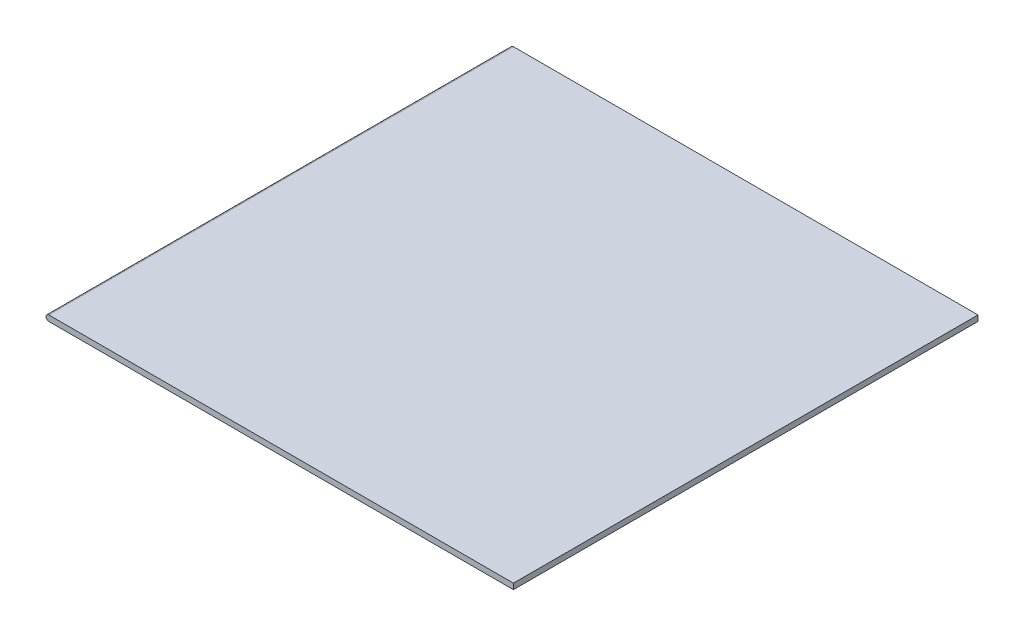
SolidWorks part; units mm, degrees
ref_plane "Спереди" through (0, 0, 0) normal (0, 0, 1) x (1, 0, 0)
ref_plane "Сверху" through (0, 0, 0) normal (0, 1, 0) x (1, 0, 0)
ref_plane "Справа" through (0, 0, 0) normal (1, 0, 0) x (0, 0, -1)
other "Configuration Table"
sketch "Эскиз1" plane through (0, 0, 0) normal (0, 1, 0) x (1, 0, 0)
  line L1 (-205, -205) -> (205, -205)
  line L2 (-205, -205) -> (-205, 205)
  line L3 (-205, 205) -> (205, 205)
  line L4 (205, -205) -> (205, 205)
  line L5 (-205, -205) -> (205, 205) construction
  line L6 (-205, 205) -> (205, -205) construction
  point P0 (0, 0)
  dimension "D1" = 410
extrude "Бобышка-Вытянуть1" add sketch "Эскиз1" along normal blind 5
sketch "Эскиз2" plane through (0, 0, 0) normal (0, 0, 1) x (1, 0, 0)
  line L0 (-205, 5) -> (-205, 0) construction
  line L1 (-205, 5) -> (-205, 0)
  circle A0 centre (-205, 2.5) radius 2.5
extrude "Бобышка-Вытянуть2" add sketch "Эскиз2" along normal through all and the other way through all contours L1 A0
